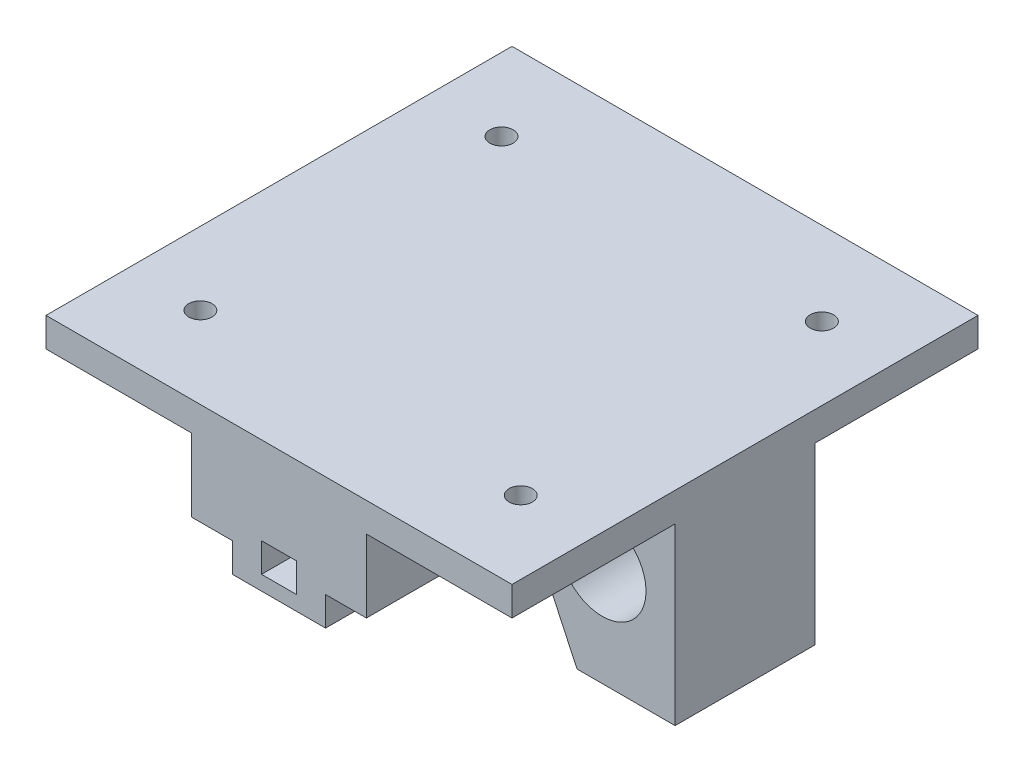
SolidWorks part; units mm, degrees
ref_plane "Front Plane" through (0, 0, 0) normal (0, 0, 1) x (1, 0, 0)
ref_plane "Top Plane" through (0, 0, 0) normal (0, 1, 0) x (1, 0, 0)
ref_plane "Right Plane" through (0, 0, 0) normal (1, 0, 0) x (0, 0, -1)
sketch "Sketch2" plane through (0, 0, 0) normal (0, 0, 1) x (1, 0, 0)
  line L14 (8, 0) -> (15, 0)
  line L16 (0, 17.5) -> (40, 17.5)
  line L17 (0, 17.5) -> (-40, 17.5)
  line L18 (23.1604, -17.5) -> (40, -17.5)
  line L19 (-23.1604, -17.5) -> (-40, -17.5)
  line L20 (-40, -17.5) -> (-40, 17.5)
  line L21 (40, 17.5) -> (40, -17.5)
  line L23 (-8, 0) -> (-15, 0)
  line L24 (-8, 0) -> (-8, -5)
  line L25 (8, 0) -> (8, -5)
  line L26 (-15, 0) -> (-23.1604, -17.5)
  line L27 (15, 0) -> (23.1604, -17.5)
  line L28 (-8, -5) -> (8, -5)
  line L29 (-3, 0) -> (-3, -2.5)
  line L30 (-3, 0) -> (-3, 2.5)
  line L31 (-3, 2.5) -> (3, 2.5)
  line L32 (3, 2.5) -> (3, 0)
  line L33 (3, 0) -> (3, -2.5)
  line L34 (3, -2.5) -> (-3, -2.5)
  circle A4 centre (-27.5, 0) radius 7.5
  circle A5 centre (27.5, 0) radius 7.5
  dimension "D1" = 40
  dimension "D7" = 5
  dimension "D2" = 35
  dimension "D4" = 40
  dimension "D9" = 5
  dimension "D10" = 2.5
  dimension "D11" = 2.5
  dimension "D12" = 115
  dimension "D13" = 115
extrude "Boss-Extrude2" add sketch "Sketch2" against normal blind 80
ref_plane "Plane2" through (0, -5, 0) normal (0, -1, 0) x (-1, 0, 0)
sketch "Sketch5" plane through (0, -5, 0) normal (0, -1, 0) x (-1, 0, 0)
  line L1 (-8, 80) -> (-8, 0) construction
  line L2 (-8, 70) -> (8, 70)
  line L3 (8, 80) -> (8, 0) construction
  line L5 (-8, 10) -> (8, 10)
  line L6 (8, 10) -> (8, 70)
  line L7 (-8, 70) -> (-8, 10)
ref_plane "Plane3" through (0, 17.5, 0) normal (0, 1, 0) x (1, 0, 0)
extrude "Cut-Extrude5" cut sketch "Sketch5" against normal blind 5
ref_plane "Plane4" through (0, 0, 0) normal (0, 0, 1) x (1, 0, 0)
sketch "Sketch6" plane through (0, 0, 0) normal (0, 0, 1) x (1, 0, 0)
  line L6 (-40, 12.5) -> (-40, -17.5)
  line L7 (-40, -17.5) -> (-23.1604, -17.5)
  line L8 (-23.1604, -17.5) -> (-15, 0)
  line L9 (-15, 0) -> (-15, 12.5)
  line L10 (-15, 12.5) -> (-40, 12.5)
  line L11 (40, 12.5) -> (40, -17.5)
  line L12 (40, -17.5) -> (23.1604, -17.5)
  line L13 (23.1604, -17.5) -> (40, -17.5) construction
  line L14 (23.1604, -17.5) -> (15, 0)
  line L15 (15, 0) -> (15, 12.5)
  line L16 (15, 12.5) -> (40, 12.5)
extrude "Cut-Extrude6" cut sketch "Sketch6" against normal blind 28
ref_plane "Plane5" through (0, 0, -80) normal (0, 0, -1) x (-1, 0, 0)
sketch "Sketch7" plane through (0, 0, -80) normal (0, 0, -1) x (-1, 0, 0)
  line L0 (-40, 12.5) -> (-40, -17.5)
  line L1 (-40, -17.5) -> (-23.1604, -17.5)
  line L2 (-23.1604, -17.5) -> (-15, 0)
  line L3 (-15, 0) -> (-23.1604, -17.5) construction
  line L4 (-15, 0) -> (-15, 12.5)
  line L5 (-15, 12.5) -> (-40, 12.5)
  line L6 (40, 12.5) -> (40, -17.5)
  line L7 (40, -17.5) -> (23.1604, -17.5)
  line L8 (23.1604, -17.5) -> (15, 0)
  line L9 (15, 0) -> (15, 12.5)
  line L10 (15, 12.5) -> (40, 12.5)
extrude "Cut-Extrude7" cut sketch "Sketch7" against normal blind 28
sketch "Sketch8" plane through (0, 17.5, 0) normal (0, 1, 0) x (1, 0, 0)
  circle A0 centre (27.5, 14) radius 2
  circle A3 centre (-27.5, 14) radius 2
  circle A5 centre (-27.5, 65.6972) radius 2
  circle A6 centre (27.5, 65.6972) radius 2
  point P18 (0, 0)
  point P19 (0, 0)
  point P22 (-27.5, 14)
  point P25 (-27.5, 65.6972)
  point P28 (26.1205, 65.6972)
extrude "Cut-Extrude8" cut sketch "Sketch8" against normal blind 5
